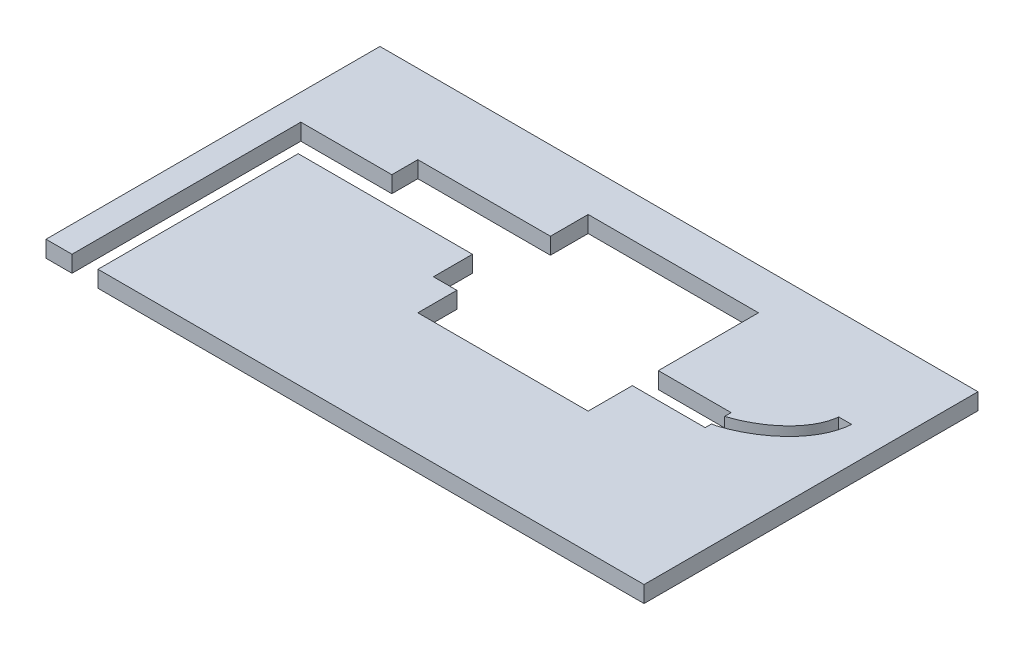
SolidWorks part; units mm, degrees
ref_plane "Front Plane" through (0, 0, 0) normal (0, 0, 1) x (1, 0, 0)
ref_plane "Top Plane" through (0, 0, 0) normal (0, 1, 0) x (1, 0, 0)
ref_plane "Right Plane" through (0, 0, 0) normal (1, 0, 0) x (0, 0, -1)
sketch "Sketch1" plane through (0, 0, 0) normal (0, 1, 0) x (1, 0, 0)
  line L0 (46.5, 29.0345) -> (115, 29.0345) construction
  line L1 (-115, -64.2155) -> (-105, -64.2155)
  line L2 (-115, -64.2155) -> (-115, 64.2155)
  line L3 (-115, 64.2155) -> (115, 64.2155)
  line L4 (115, -64.2155) -> (115, 64.2155)
  line L5 (-115, -64.2155) -> (115, 64.2155) construction
  line L6 (-115, 64.2155) -> (115, -64.2155) construction
  line L7 (-95, -64.2155) -> (-95, 12.7845)
  line L8 (-95, 12.7845) -> (-28, 12.7845)
  line L9 (-28, 12.7845) -> (-28, -2.2155)
  line L10 (-28, -2.2155) -> (-19, -2.2155)
  line L11 (-19, -2.2155) -> (-19, -17.2155)
  line L12 (-19, -17.2155) -> (46.5, -17.2155)
  line L13 (46.5, -17.2155) -> (46.5, -0.2155)
  line L14 (46.5, -0.2155) -> (74.5, -0.2155)
  line L15 (74.5, 2.2845) -> (75.9569, 2.5015)
  line L16 (96.6106, 29.0345) -> (101.5945, 29.0345)
  line L17 (-95, -64.2155) -> (115, -64.2155)
  line L18 (74.5, -0.2155) -> (74.5, 2.2845)
  line L19 (46.5, 9.7845) -> (46.5, 48.2845)
  line L20 (46.5, 48.2845) -> (-19, 48.2845)
  line L21 (-19, 48.2845) -> (-19, 33.7845)
  line L22 (-19, 33.7845) -> (-70, 33.7845)
  line L23 (-70, 33.7845) -> (-70, 23.7845)
  line L24 (-70, 23.7845) -> (-105, 23.7845)
  line L25 (-105, 23.7845) -> (-105, -64.2155)
  line L26 (13.75, 48.2845) -> (13.75, -17.2155) construction
  line L27 (74.5, 7.2845) -> (74.5, 9.7845)
  line L28 (74.5, 9.7845) -> (46.5, 9.7845)
  spline S0 degree 3 poles (74.5, 7.2845) (78.9418, 8.68) (89.5981, 14.1604) (96.0619, 23.1895) (96.6106, 29.0345) knots 0 0 0 0 0.139776 0.343964 0.343964 0.343964 0.343964
  spline S1 degree 3 poles (75.9569, 2.5015) (80.4401, 3.907) (86.917, 7.0921) (94.0891, 13.1463) (98.4145, 18.5796) (100.8648, 24.0204) (101.4972, 27.6801) (101.5945, 29.0345) knots 0 0 0 0 0.125 0.1875 0.25 0.3125 0.34813 0.34813 0.34813 0.34813
  point P0 (0, 0)
  point P18 (115, 29.0345)
  point P30 (46.5, 29.0345)
  dimension "D1" = 230
  dimension "D3" = 10
  dimension "D4" = 11
  dimension "D5" = 10
  dimension "D6" = 51
  dimension "D7" = 65.5
  dimension "D8" = 9
  dimension "D9" = 15
  dimension "D10" = 15
  dimension "D11" = 2.5
  dimension "D12" = 17
  dimension "D13" = 28
  dimension "D14" = 88
  dimension "D15" = 35
  dimension "D16" = 19
  dimension "D17" = 10
  dimension "D18" = 128.431
  dimension "D19" = 1.473
  dimension "D23" = 17.2155
extrude "Boss-Extrude1" add sketch "Sketch1" along normal blind 6.35
